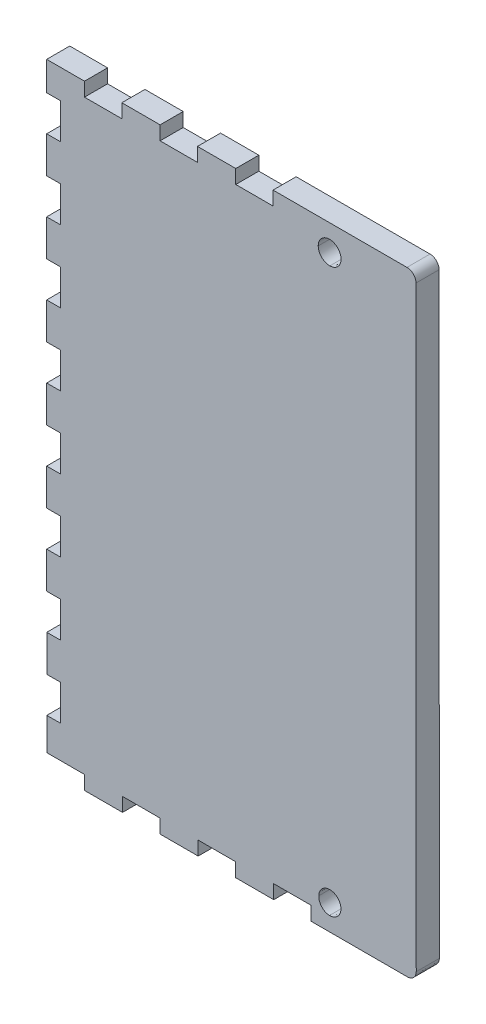
SolidWorks part; units mm, degrees
material "Perspex (TM) GS Acrylic Cast Sheet"
ref_plane "Front Plane" through (0, 0, 0) normal (0, 0, 1) x (1, 0, 0)
ref_plane "Top Plane" through (0, 0, 0) normal (0, 1, 0) x (1, 0, 0)
ref_plane "Right Plane" through (0, 0, 0) normal (1, 0, 0) x (0, 0, -1)
sketch "Sketch2" plane through (0, 0, 0) normal (0, 0, 1) x (1, 0, 0)
  line L0 (0.0263, 1.835) -> (0.0263, -1.1644) construction
  line L1 (0.0263, -1.1644) -> (8.1409, -1.1644) construction
  line L2 (3, 125.6051) -> (0, 125.6051)
  line L3 (3, 8.8413) -> (0.0263, 8.8413)
  line L4 (0, 131.8769) -> (0, 125.6051)
  line L5 (0.0263, 8.8413) -> (0.0263, 1.835)
  line L6 (78.0342, 131.8709) -> (49.032, 131.8709)
  line L7 (78.0868, -1.1644) -> (57.2734, -1.1644)
  line L8 (79.9982, 129.9141) -> (80.0489, 0.7693)
  line L9 (61.249, 128.7556) -> (61.249, 1.9108) construction
  line L349 (8.1904, 128.8769) -> (8.1904, 131.8769)
  line L350 (8.1904, 128.8769) -> (16.2813, 128.8769)
  line L351 (16.2813, 128.8769) -> (16.2813, 131.8769)
  line L352 (16.2813, 131.8769) -> (24.5722, 131.8769)
  line L353 (24.5722, 128.8769) -> (24.5722, 131.8769)
  line L354 (24.5722, 128.8769) -> (32.6631, 128.8769)
  line L355 (32.6631, 128.8769) -> (32.6631, 131.8769)
  line L356 (32.6631, 131.8769) -> (40.954, 131.8769)
  line L357 (40.954, 128.8769) -> (40.954, 131.8769)
  line L358 (40.954, 128.8769) -> (49.032, 128.8769)
  line L359 (49.032, 128.8769) -> (49.032, 131.8709)
  line L366 (3, 125.6051) -> (3, 117.9142)
  line L367 (3, 117.9142) -> (0, 117.9142)
  line L368 (0, 117.9142) -> (0, 110.0232)
  line L369 (3, 110.0232) -> (0, 110.0232)
  line L370 (3, 110.0232) -> (3, 102.3323)
  line L371 (3, 102.3323) -> (0, 102.3323)
  line L372 (0, 102.3323) -> (0, 94.4414)
  line L373 (3, 94.4414) -> (0, 94.4414)
  line L374 (3, 94.4414) -> (3, 86.7505)
  line L375 (3, 86.7505) -> (0, 86.7505)
  line L376 (0, 86.7505) -> (0, 78.8596)
  line L377 (3, 78.8596) -> (0, 78.8596)
  line L378 (3, 78.8596) -> (3, 71.1686)
  line L379 (3, 71.1686) -> (0, 71.1686)
  line L380 (0, 71.1686) -> (0, 63.2777)
  line L381 (3, 63.2777) -> (0, 63.2777)
  line L382 (3, 63.2777) -> (3, 55.5868)
  line L383 (3, 55.5868) -> (0, 55.5868)
  line L384 (0, 55.5868) -> (0, 47.6959)
  line L385 (3, 47.6959) -> (0, 47.6959)
  line L386 (3, 47.6959) -> (3, 40.005)
  line L387 (3, 40.005) -> (0, 40.005)
  line L388 (0, 40.005) -> (0, 32.114)
  line L389 (3, 32.114) -> (0, 32.114)
  line L390 (3, 32.114) -> (3, 24.4231)
  line L391 (3, 24.4231) -> (0.0263, 24.4231)
  line L392 (0.0263, 24.4231) -> (0.0263, 16.5322)
  line L393 (3, 16.5322) -> (0.0263, 16.5322)
  line L394 (3, 16.5322) -> (3, 8.8413)
  line L397 (0, 131.8769) -> (8.1904, 131.8769)
  line L398 (0.0263, 1.835) -> (8.1409, 1.835)
  line L399 (8.1409, -1.1644) -> (8.1409, 1.835)
  line L400 (8.1409, -1.1644) -> (16.4318, -1.1644)
  line L401 (16.4318, -1.1644) -> (16.4318, 1.835)
  line L402 (16.4318, 1.835) -> (24.5228, 1.835)
  line L403 (24.5228, -1.165) -> (24.5228, 1.835)
  line L404 (24.5228, -1.165) -> (32.8136, -1.165)
  line L405 (32.8136, -1.165) -> (32.8136, 1.835)
  line L406 (32.8136, 1.835) -> (40.9046, 1.835)
  line L407 (40.9046, -1.165) -> (40.9046, 1.835)
  line L408 (40.9046, -1.165) -> (49.1825, -1.165)
  line L409 (49.1825, -1.165) -> (49.1825, 1.835)
  line L410 (49.1825, 1.835) -> (57.2734, 1.835)
  line L411 (57.2734, -1.1644) -> (57.2734, 1.835)
  spline S64 degree 3 poles (78.0868, -1.1644) (79.1711, -1.1644) (80.0501, -0.2854) (80.0489, 0.7693) knots 0 0 0 0 1 1 1 1
  spline S65 degree 3 poles (78.0342, 131.8709) (79.1185, 131.8709) (79.9975, 130.9919) (79.9982, 129.9141) knots 0 0 0 0 1 1 1 1
  spline S66 degree 3 poles (58.9425, 4.4571) (58.8764, 3.1169) (59.91, 1.9769) (61.249, 1.9108) knots 0 0 0 0 1 1 1 1
  spline S67 degree 3 poles (61.249, 1.9108) (62.6171, 1.904) (63.7335, 3.0085) (63.7404, 4.3778) knots 0 0 0 0 1 1 1 1
  spline S68 degree 3 poles (63.7404, 4.3778) (63.7471, 5.7121) (62.6695, 6.7997) (61.3357, 6.8064) knots 0 0 0 0 1 1 1 1
  spline S69 degree 3 poles (61.3357, 6.8064) (60.027, 6.8185) (58.9545, 5.7664) (58.9425, 4.4571) knots 0 0 0 0 1 1 1 1
  spline S70 degree 3 poles (58.8137, 126.2945) (58.8209, 124.9103) (59.9497, 123.794) (61.3327, 123.8011) knots 0 0 0 0 1 1 1 1
  spline S71 degree 3 poles (61.3327, 123.8011) (62.6838, 123.8143) (63.7703, 124.9213) (63.7571, 126.2735) knots 0 0 0 0 1 1 1 1
  spline S72 degree 3 poles (63.7571, 126.2735) (63.75, 127.6512) (62.626, 128.7627) (61.249, 128.7556) knots 0 0 0 0 1 1 1 1
  spline S73 degree 3 poles (61.249, 128.7556) (59.8979, 128.7484) (58.8065, 127.6462) (58.8137, 126.2945) knots 0 0 0 0 1 1 1 1
  point P0 (0, 128.741)
extrude "Boss-Extrude1" add sketch "Sketch2" along normal blind 5
